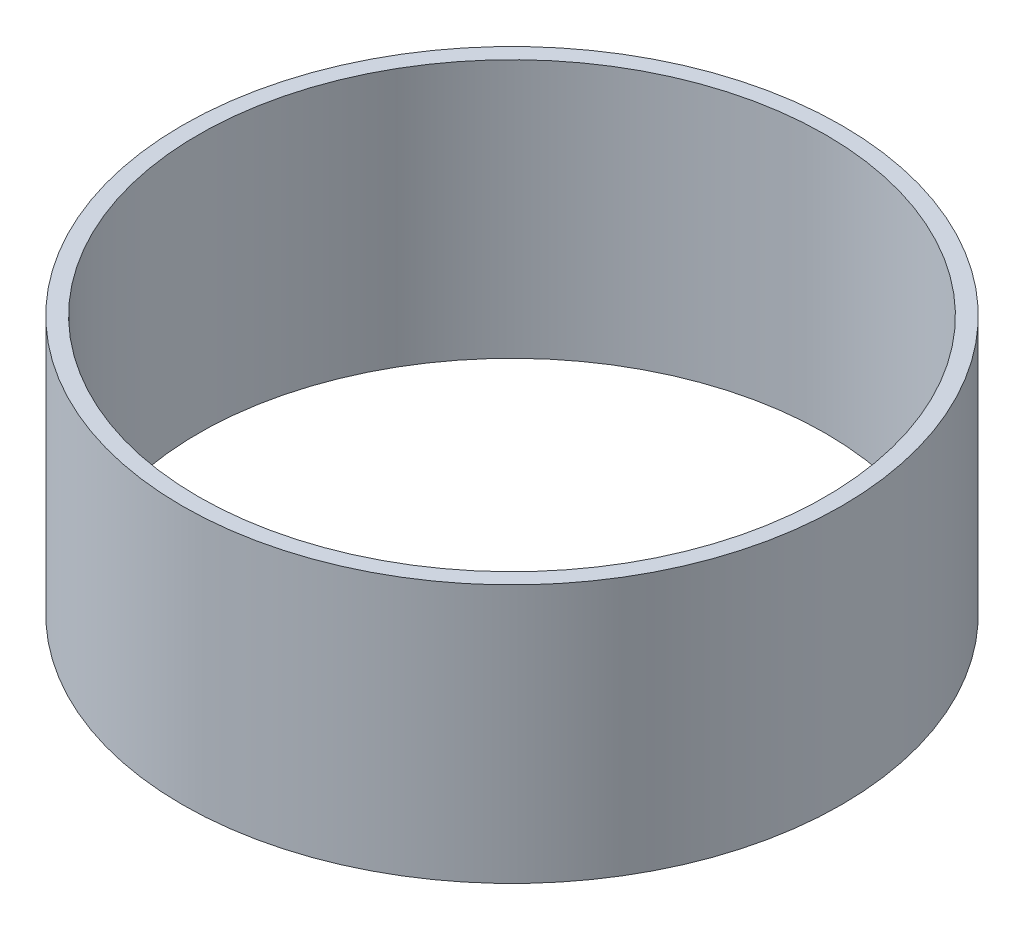
SolidWorks part; units mm, degrees
material "橡胶"
ref_plane "前视基准面" through (0, 0, 0) normal (0, 0, 1) x (1, 0, 0)
ref_plane "上视基准面" through (0, 0, 0) normal (0, 1, 0) x (1, 0, 0)
ref_plane "右视基准面" through (0, 0, 0) normal (1, 0, 0) x (0, 0, -1)
sketch "草图1" plane through (0, 0, 0) normal (0, 1, 0) x (1, 0, 0)
  circle A0 centre (0, 0) radius 51
  circle A1 centre (0, 0) radius 48.5
  dimension "D1" = 97
  dimension "D2" = 102
extrude "凸台-拉伸1" add sketch "草图1" along normal mid plane 40
